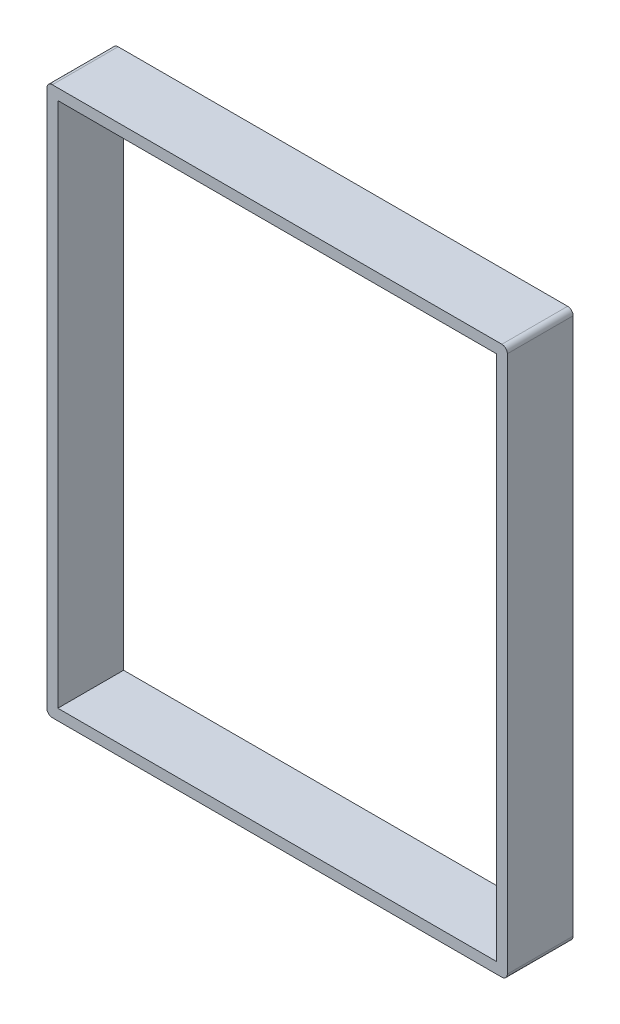
SolidWorks part; units mm, degrees
ref_plane "Front Plane" through (0, 0, 0) normal (0, 0, 1) x (1, 0, 0)
ref_plane "Top Plane" through (0, 0, 0) normal (0, 1, 0) x (1, 0, 0)
ref_plane "Right Plane" through (0, 0, 0) normal (1, 0, 0) x (0, 0, -1)
sketch "Sketch1" plane through (0, 0, 0) normal (0, 0, 1) x (1, 0, 0)
  line L1 (-266.7, -317.5) -> (266.7, -317.5)
  line L2 (-266.7, -317.5) -> (-266.7, 317.5)
  line L3 (-266.7, 317.5) -> (266.7, 317.5)
  line L4 (266.7, -317.5) -> (266.7, 317.5)
  line L5 (-266.7, -317.5) -> (266.7, 317.5) construction
  line L6 (-266.7, 317.5) -> (266.7, -317.5) construction
  point P0 (0, 0)
  dimension "D1" = 533.4
  dimension "D2" = 635
extrude "Boss-Extrude1" add sketch "Sketch1" along normal blind 76.2
sketch "Sketch2" plane through (0, 0, 76.2) normal (0, 0, 1) x (1, 0, 0)
  line L1 (-254, -304.8) -> (254, -304.8)
  line L2 (-254, -304.8) -> (-254, 304.8)
  line L3 (-254, 304.8) -> (254, 304.8)
  line L4 (254, -304.8) -> (254, 304.8)
  line L5 (-254, -304.8) -> (254, 304.8) construction
  line L6 (-254, 304.8) -> (254, -304.8) construction
  point P0 (0, 0)
  dimension "D1" = 508
  dimension "D2" = 609.6
extrude "Cut-Extrude1" cut sketch "Sketch2" against normal through all
fillet "Fillet1" radius 6.35 4 edges at (-266.7, 317.5, 38.1) (266.7, 317.5, 38.1) (266.7, -317.5, 38.1) (-266.7, -317.5, 38.1)
